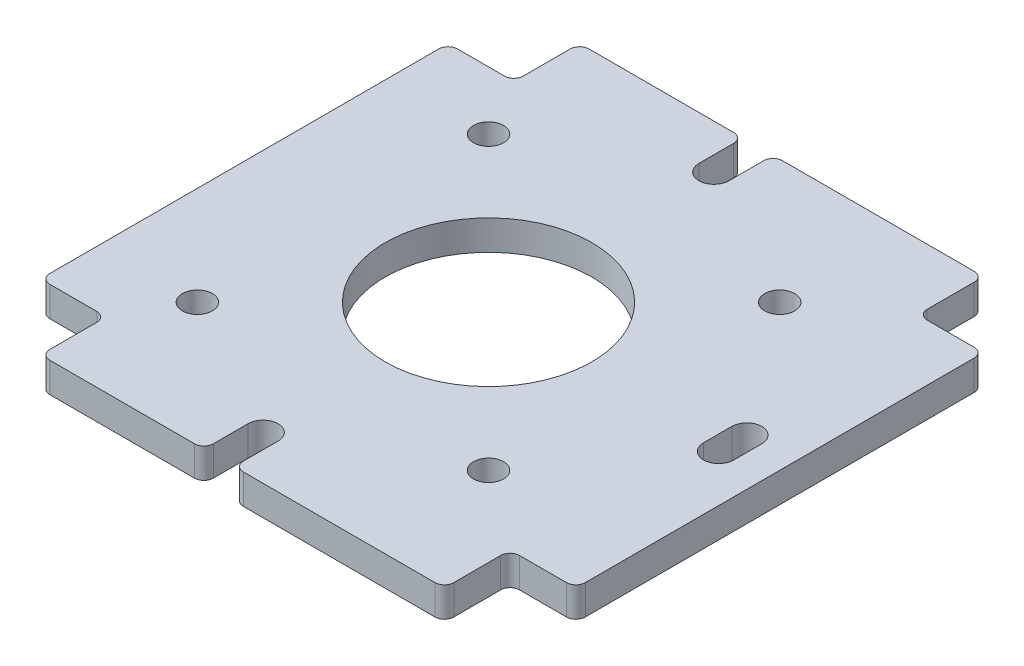
SolidWorks part; units mm, degrees
material "AISI 1045 Steel, cold drawn"
ref_plane "Front Plane" through (0, 0, 0) normal (0, 0, 1) x (1, 0, 0)
ref_plane "Top Plane" through (0, 0, 0) normal (0, 1, 0) x (1, 0, 0)
ref_plane "Right Plane" through (0, 0, 0) normal (1, 0, 0) x (0, 0, -1)
sketch "Sketch1" plane through (0, 0, 0) normal (0, 1, 0) x (1, 0, 0)
  line L1 (15.5, -15.5) -> (-15.5, -15.5) construction
  line L2 (15.5, -15.5) -> (15.5, 15.5) construction
  line L3 (15.5, 15.5) -> (-15.5, 15.5) construction
  line L4 (-15.5, -15.5) -> (-15.5, 15.5) construction
  line L5 (15.5, -15.5) -> (-15.5, 15.5) construction
  line L6 (15.5, 15.5) -> (-15.5, -15.5) construction
  line L7 (21, -21) -> (-21, -21)
  line L8 (21, -21) -> (21, 21)
  line L9 (21, 21) -> (-21, 21)
  line L10 (-21, -21) -> (-21, 21)
  line L11 (21, -21) -> (-21, 21) construction
  line L12 (21, 21) -> (-21, -21) construction
  circle A0 centre (0, 0) radius 11
  dimension "D1" = 22
  dimension "D2" = 31
  dimension "D3" = 42
extrude "Boss-Extrude1" add sketch "Sketch1" along normal mid plane 3.175
hole_wizard "M3 Clearance Hole1" positions "Sketch2" profile "Sketch3" hole size "M3" standard "ANSI Metric" end condition through all
sketch "Sketch2" plane through (0, 1.5875, 0) normal (0, 1, 0) x (1, 0, 0)
  point P0 (-15.5, 15.5)
  point P3 (15.5, 15.5)
  point P6 (15.5, -15.5)
  point P9 (-15.5, -15.5)
sketch "Sketch3" plane through (-15.5, 1.5875, -15.5) normal (1, 0, 0) x (0, 0, 1)
  line L0 (0, 0) -> (0, 3.175)
  line L1 (0, 3.175) -> (1.6, 3.175)
  line L2 (1.6, 3.175) -> (1.6, 0)
  line L5 (1.6, 0) -> (0, 0)
  line L11 (0, -6.35) -> (0, 107.95) construction
  dimension "Thru Hole Dia." = 3.2
  dimension "Thru Hole Depth" = 3.175
sketch "Sketch4" plane through (0, 1.5875, 0) normal (0, 1, 0) x (1, 0, 0)
  line L0 (0, -24) -> (0, -29) construction
  line L1 (1.6, -24) -> (1.6, -28.7)
  line L2 (-1.6, -24) -> (-1.6, -28.7)
  line L3 (26, 1.5) -> (26, -1.5) construction
  line L4 (27.6, 1.5) -> (27.6, -1.5)
  line L5 (24.4, 1.5) -> (24.4, -1.5)
  line L6 (-19, -21) -> (14, -21)
  line L9 (-21, -21) -> (21, -21) construction
  line L10 (-21, 21) -> (-26, 21)
  line L11 (21, -21) -> (21, 21) construction
  line L12 (21, 0) -> (-21, 0) construction
  line L13 (0, 24) -> (0, 29) construction
  line L14 (1.6, 28.7) -> (14, 28.7)
  line L15 (-19, -21) -> (-19, -28.7)
  line L16 (-19, -28.7) -> (-1.6, -28.7)
  line L17 (14, -28.7) -> (14, -21)
  line L18 (-21, 21) -> (-21, -21) construction
  line L19 (1.6, -28.7) -> (14, -28.7)
  line L20 (14, 28.7) -> (14, 21)
  line L21 (-19, 28.7) -> (-1.6, 28.7)
  line L22 (-19, 21) -> (-19, 28.7)
  line L23 (-19, 21) -> (14, 21)
  line L24 (-1.6, 24) -> (-1.6, 28.7)
  line L25 (1.6, 24) -> (1.6, 28.7)
  line L26 (21, 14) -> (31, 14)
  line L27 (31, 14) -> (31, -14)
  line L28 (31, -14) -> (21, -14)
  line L29 (21, 21) -> (-21, 21) construction
  line L30 (21, 14) -> (21, -14)
  line L31 (-26, 21) -> (-26, -21)
  line L32 (-26, -21) -> (-21, -21)
  line L33 (-21, 21) -> (-21, -21)
  arc A0 (1.6, -24) -> (-1.6, -24) centre (0, -24) ccw
  arc A2 (27.6, 1.5) -> (24.4, 1.5) centre (26, 1.5) ccw
  arc A3 (24.4, -1.5) -> (27.6, -1.5) centre (26, -1.5) ccw
  arc A6 (1.6, 24) -> (-1.6, 24) centre (0, 24) cw
  point P10 (26, 0)
  point P17 (0, 0)
  dimension "D1" = 1.6
  dimension "D12" = 1.6
  dimension "D2" = 3
  dimension "D3" = 5
  dimension "D4" = 10
  dimension "D5" = 5
  dimension "D6" = 7.7
  dimension "D7" = 7
  dimension "D8" = 7
  dimension "D9" = 7
  dimension "D10" = 7
  dimension "D11" = 3
  dimension "D13" = 5
extrude "Boss-Extrude2" add sketch "Sketch4" against normal up to vertex (3.175 mm away) up to point (21, -1.5875, -21)
sketch "Sketch5" plane through (0, 1.5875, 0) normal (0, 1, 0) x (1, 0, 0)
  line L0 (21, -14) -> (31, -14) construction
  line L17 (31, 14) -> (21, 14)
  line L18 (31, 14) -> (31, 21)
  line L19 (31, 21) -> (21, 21)
  line L20 (21, 14) -> (21, 21)
  line L21 (14, 28.7) -> (24, 28.7)
  line L22 (14, 28.7) -> (14, 21)
  line L23 (14, 21) -> (24, 21)
  line L24 (24, 28.7) -> (24, 21)
  line L25 (31, -14) -> (21, -14)
  line L26 (31, -14) -> (31, -21)
  line L27 (31, -21) -> (21, -21)
  line L28 (21, -14) -> (21, -21)
  line L29 (31, -14) -> (31, 14) construction
  line L30 (-19, -21) -> (-19, -28.7) construction
  line L31 (14, -28.7) -> (24, -28.7)
  line L32 (14, -28.7) -> (14, -21)
  line L33 (14, -21) -> (24, -21)
  line L34 (24, -28.7) -> (24, -21)
  line L35 (-26, -21) -> (-19, -21)
  line L36 (-26, -21) -> (-26, -21.7)
  line L37 (-26, -21.7) -> (-19, -21.7)
  line L38 (-19, -21) -> (-19, -21.7)
  line L39 (-19, 28.7) -> (-19, 21) construction
  line L40 (-26, 21) -> (-19, 21)
  line L41 (-26, 21) -> (-26, 21.7)
  line L42 (-26, 21.7) -> (-19, 21.7)
  line L43 (-19, 21) -> (-19, 21.7)
  line L44 (-1.6, 28.7) -> (-19, 28.7) construction
  line L45 (31, 21) -> (24, 21)
  line L46 (31, 21) -> (31, 21.7)
  line L47 (31, 21.7) -> (24, 21.7)
  line L48 (24, 21) -> (24, 21.7)
  line L49 (31, -21) -> (24, -21)
  line L50 (31, -21) -> (31, -21.7)
  line L51 (31, -21.7) -> (24, -21.7)
  line L52 (24, -21) -> (24, -21.7)
  line L53 (-19, -28.7) -> (-1.6, -28.7) construction
  line L54 (-26, 21) -> (-26, -21) construction
  line L55 (-19, 21) -> (-26, 21) construction
  dimension "D1" = 7
  dimension "D2" = 7
  dimension "D3" = 7
extrude "Boss-Extrude3" add sketch "Sketch5" against normal up to surface (3.175 mm away)
fillet "Fillet1" radius 1 16 edges at (-1.6, 0, 28.7) (1.6, 0, 28.7) (-19, 0, 28.7) (1.6, 0, -28.7) (-1.6, 0, -28.7) (-19, 0, -28.7) (24, 0, -28.7) (24, 0, 28.7) (-26, 0, 21.7) (-19, 0, 21.7) (24, 0, 21.7) (31, 0, 21.7) (31, 0, -21.7) (24, 0, -21.7) (-19, 0, -21.7) (-26, 0, -21.7)
